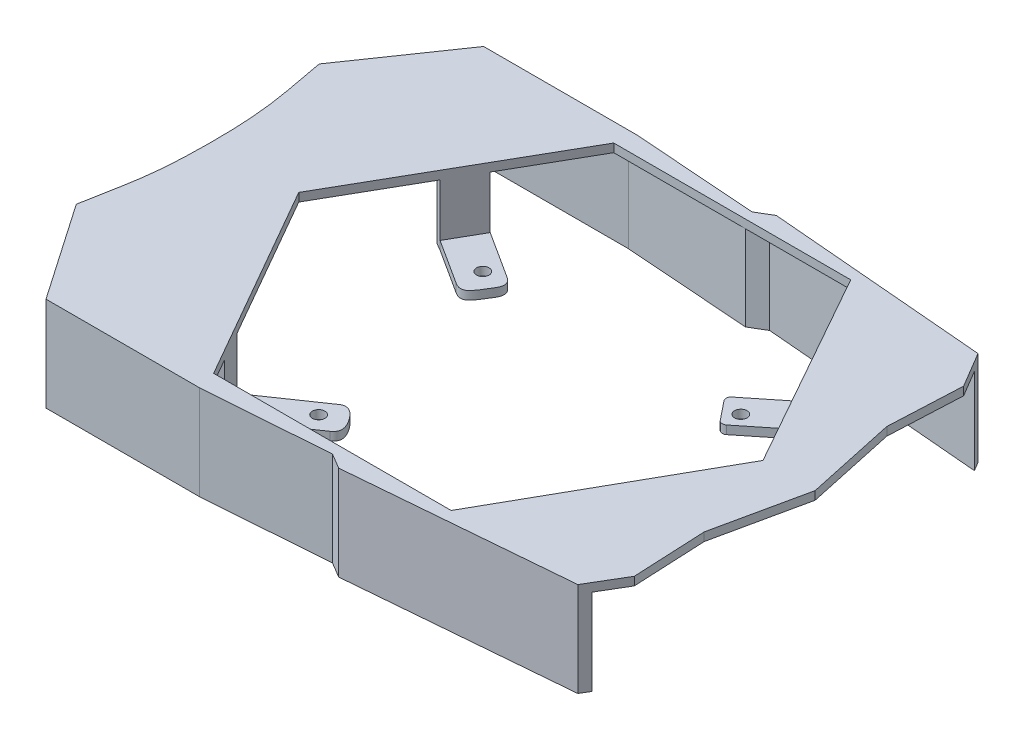
SolidWorks part; units mm, degrees
ref_plane "Front Plane" through (0, 0, 0) normal (0, 0, 1) x (1, 0, 0)
ref_plane "Top Plane" through (0, 0, 0) normal (0, 1, 0) x (1, 0, 0)
ref_plane "Right Plane" through (0, 0, 0) normal (1, 0, 0) x (0, 0, -1)
ref_plane "Plane1" through (0, -1, 0) normal (0, 1, 0) x (1, 0, 0)
sketch "Sketch2" plane through (0, 0, 0) normal (0, 1, 0) x (1, 0, 0)
  line L0 (-43.2305, 45.2477) -> (-32.0512, 38.0628)
  line L1 (-59.8574, 16.2204) -> (-32.6384, -31.2986) construction
  line L2 (-32.6384, -31.2986) -> (24.1663, -31.2986) construction
  line L3 (24.1663, -31.2986) -> (50.8521, 16.2204) construction
  line L4 (50.8521, 16.2204) -> (-59.8574, 16.2204) construction
  line L5 (24.1663, 63.7393) -> (50.8521, 16.2204) construction
  line L6 (-59.8574, 16.2204) -> (-32.6384, 63.7393) construction
  line L7 (-32.6384, 63.7393) -> (24.1663, 63.7393) construction
  line L8 (-47.5869, 37.6421) -> (-36.7839, 30.699)
  line L9 (-43.2305, 45.2477) -> (-47.5869, 37.6421)
  line L10 (-36.7839, 30.699) -> (-32.0512, 38.0628) construction
  line L11 (-34.4176, 34.3809) -> (-25.2787, 28.5074) construction
  line L12 (-32.1914, 32.9502) -> (-30.5732, 35.4679) construction
  line L13 (-36.1854, -25.1061) -> (-21.2791, -14.8713)
  line L14 (-25.7957, -8.2932) -> (-40.1647, -18.159)
  line L15 (-21.2791, -14.8713) -> (-25.7957, -8.2932) construction
  line L16 (-23.5374, -11.5822) -> (-16.1776, -6.5289) construction
  line L17 (29.2117, -22.3145) -> (14.8692, -14.26)
  line L18 (14.6527, -12.323) -> (19.1605, -8.2533)
  line L19 (20.5522, -8.0977) -> (33.2051, -15.2033)
  line L20 (35.9563, 42.7452) -> (24.663, 33.699)
  line L21 (31.8845, 49.9957) -> (19.5337, 40.1025)
  line L22 (22.9762, 33.8854) -> (19.3473, 38.4157)
  line L23 (31.8845, 49.9957) -> (35.9563, 42.7452)
  line L24 (29.2117, -22.3145) -> (33.2051, -15.2033)
  line L25 (-40.1647, -18.159) -> (-36.1854, -25.1061)
  circle A0 centre (-36.0903, 36.3367) radius 1.5
  circle A1 centre (24.1663, 37.603) radius 1.5
  circle A2 centre (19.9954, -13.2346) radius 1.5
  circle A3 centre (-26.0794, -12.8178) radius 1.5
  arc A4 (20.5522, -8.0977) -> (19.1605, -8.2533) centre (19.9646, -9.144) ccw
  arc A5 (14.8692, -14.26) -> (14.6527, -12.323) centre (15.4568, -13.2137) cw
  arc A6 (19.5337, 40.1025) -> (19.3473, 38.4157) centre (20.2839, 39.1659) ccw
  arc A7 (24.663, 33.699) -> (22.9762, 33.8854) centre (23.9128, 34.6356) cw
  spline S0 degree 3 poles (-32.0512, 38.0628) (-29.6539, 36.522) (-32.3592, 33.058) (-34.3933, 29.1626) (-36.7839, 30.699) knots 0 0 0 0 0.5 1 1 1 1
  spline S1 degree 3 poles (-25.7957, -8.2932) (-24.1437, -7.1589) (-21.1111, -9.9163) (-19.5185, -13.6625) (-21.2791, -14.8713) knots 0 0 0 0 0.5 1 1 1 1
  dimension "D1" = 3
  dimension "D2" = 3
  dimension "D3" = 3
  dimension "D4" = 3
  dimension "D19" = 1.2
  dimension "D20" = 1.2
  dimension "D5" = 71.1821
  dimension "D6" = 19.9954
  dimension "D7" = 24.1663
  dimension "D8" = 26.0794
  dimension "D9" = 37.603
  dimension "D10" = 110.7095
  dimension "D11" = 36.3367
  dimension "D12" = 60.196
  dimension "D13" = 74.8527
  dimension "D14" = 31.2986
  dimension "D15" = 36.0903
  dimension "D16" = 32.6384
  dimension "D17" = 24.1663
  dimension "D18" = 50.8521
extrude "Boss-Extrude3" add sketch "Sketch2" along normal blind 2
sketch "Sketch7" plane through (0, 0, 0) normal (0, -1, 0) x (1, 0, 0)
  line L0 (-36.1854, 25.1061) -> (-37.9209, 26.1002)
  line L1 (-37.9209, 26.1002) -> (-41.9002, 19.1531)
  line L2 (-41.9002, 19.1531) -> (-40.1647, 18.159)
  line L3 (-40.1647, 18.159) -> (-36.1854, 25.1061) construction
  line L4 (-40.1647, 18.159) -> (-36.1854, 25.1061) construction
  line L5 (-36.1854, 25.1061) -> (-40.1647, 18.159)
  line L6 (-43.2305, -45.2477) -> (-47.5869, -37.6421)
  line L7 (-43.2305, -45.2477) -> (-44.9659, -46.2417)
  line L8 (-47.5869, -37.6421) -> (-49.3224, -38.6362)
  line L9 (-44.9659, -46.2417) -> (-49.3224, -38.6362)
  line L10 (31.8845, -49.9957) -> (35.9563, -42.7452)
  line L11 (31.8845, -49.9957) -> (33.6283, -50.975)
  line L12 (35.9563, -42.7452) -> (37.7001, -43.7245)
  line L13 (33.6283, -50.975) -> (37.7001, -43.7245)
  line L14 (29.2117, 22.3145) -> (33.2051, 15.2033)
  line L15 (29.2117, 22.3145) -> (30.9555, 23.2938)
  line L16 (33.2051, 15.2033) -> (34.949, 16.1826)
  line L17 (30.9555, 23.2938) -> (34.949, 16.1826)
  line L18 (29.2117, 22.3145) -> (33.2051, 15.2033) construction
  line L19 (33.2051, 15.2033) -> (20.5522, 8.0977) construction
  dimension "D1" = 2
  dimension "D2" = 2
  dimension "D3" = 2
  dimension "D4" = 2
extrude "Boss-Extrude7" add sketch "Sketch7" against normal blind 14.5
sketch "Sketch8" plane through (0, 14.5, 0) normal (0, 1, 0) x (1, 0, 0)
  line L1 (-59.8574, 16.2204) -> (-40.1647, -18.159)
  line L2 (-40.1647, -18.159) -> (-36.1854, -25.1061) construction
  line L3 (-59.8574, 16.2204) -> (50.8334, 16.2204) construction
  line L4 (50.8334, 16.2204) -> (23.9934, -31.2876)
  line L5 (23.9934, -31.2876) -> (-32.6446, -31.2876)
  line L6 (-32.6446, -31.2876) -> (-40.1647, -18.159)
  line L7 (-83.939, -12.7437) -> (-67.9484, -35.9533)
  line L8 (-67.9484, -35.9533) -> (-31.3331, -35.9533)
  line L9 (-31.3331, -35.9533) -> (-1.8009, -33.7876)
  line L10 (-1.8009, -33.7876) -> (1.845, -35.9533)
  line L11 (1.845, -35.9533) -> (54.3929, -31.4855)
  line L12 (54.3929, -31.4855) -> (59.4091, -23.0409)
  line L13 (59.4091, -23.0409) -> (58.5857, -5.538)
  line L14 (58.5857, -5.538) -> (63.2776, 16.2204)
  line L15 (-83.939, -12.7437) -> (-82.229, -3.4871)
  line L16 (-59.8574, 16.2204) -> (-80.6714, 16.2204) construction
  line L17 (-80.6714, 17.2536) -> (-80.6714, 15.1871)
  line L18 (-83.939, 45.1845) -> (-82.229, 35.9279)
  line L19 (58.5857, 37.9787) -> (63.2776, 16.2204)
  line L20 (59.4091, 55.4817) -> (58.5857, 37.9787)
  line L21 (54.3929, 63.9263) -> (59.4091, 55.4817)
  line L22 (1.845, 68.3941) -> (54.3929, 63.9263)
  line L23 (-1.8009, 66.2284) -> (1.845, 68.3941)
  line L24 (-31.3331, 68.3941) -> (-1.8009, 66.2284)
  line L25 (-67.9484, 68.3941) -> (-31.3331, 68.3941)
  line L26 (-83.939, 45.1845) -> (-67.9484, 68.3941)
  line L27 (-32.5028, 63.976) -> (-59.8574, 16.2204)
  line L28 (23.9939, 63.976) -> (-32.5028, 63.976)
  line L29 (50.8334, 16.2204) -> (23.9939, 63.976)
  line L31 (-43.2305, 45.2477) -> (-47.5869, 37.6421) construction
  spline S0 degree 3 poles (-82.229, -3.4871) (-81.0799, 2.7333) (-80.6714, 8.9003) (-80.6714, 15.1871) knots 0 0 0 0 1 1 1 1
  spline S1 degree 3 poles (-82.229, 35.9279) (-81.0799, 29.7075) (-80.6714, 23.5404) (-80.6714, 17.2536) knots 0 0 0 0 1 1 1 1
  dimension "D1" = 2.5
  dimension "D2" = 50.008
  dimension "D3" = 47.7556
  dimension "D4" = 52.1737
  dimension "D5" = 1.0332
extrude "Boss-Extrude8" add sketch "Sketch8" along normal blind 2
sketch "Sketch9" plane through (0, 14.5, 0) normal (0, -1, 0) x (1, 0, 0)
  line L11 (-67.9484, -66.3941) -> (-69.3263, -66.3941)
  line L12 (-67.9484, -68.3941) -> (-83.939, -45.1845) construction
  line L13 (54.2235, -61.9335) -> (55.6486, -61.8123)
  line L14 (59.4091, -55.4817) -> (54.3929, -63.9263) construction
  line L15 (54.2235, -61.9335) -> (2.3148, -66.3469)
  line L16 (2.3148, -66.3469) -> (-1.3201, -64.1877)
  line L17 (-1.3201, -64.1877) -> (-31.4064, -66.3941)
  line L18 (-31.4064, -66.3941) -> (-67.9484, -66.3941)
  line L19 (54.2235, -61.9335) -> (2.3148, -66.3469)
  line L20 (2.3148, -66.3469) -> (-1.3201, -64.1877)
  line L21 (-1.3201, -64.1877) -> (-31.4064, -66.3941)
  line L22 (-31.4064, -66.3941) -> (-67.9484, -66.3941)
  line L33 (-67.9484, 33.9533) -> (-69.3263, 33.9533)
  line L34 (-83.939, 12.7437) -> (-67.9484, 35.9533) construction
  line L35 (54.2235, 29.4927) -> (55.6486, 29.3715)
  line L36 (54.3929, 31.4855) -> (59.4091, 23.0409) construction
  line L37 (2.3148, 33.9062) -> (54.2235, 29.4927)
  line L38 (-1.3201, 31.747) -> (2.3148, 33.9062)
  line L39 (-31.4064, 33.9533) -> (-1.3201, 31.747)
  line L40 (-67.9484, 33.9533) -> (-31.4064, 33.9533)
  line L41 (2.3148, 33.9062) -> (54.2235, 29.4927)
  line L42 (-1.3201, 31.747) -> (2.3148, 33.9062)
  line L43 (-31.4064, 33.9533) -> (-1.3201, 31.747)
  line L44 (-67.9484, 33.9533) -> (-31.4064, 33.9533)
  line L45 (-69.3263, 33.9533) -> (-67.9484, 35.9533)
  line L46 (-67.9484, 35.9533) -> (-31.3331, 35.9533)
  line L47 (-31.3331, 35.9533) -> (-1.8009, 33.7876) construction
  line L48 (-67.9484, 35.9533) -> (-31.3331, 35.9533) construction
  line L49 (-31.3331, 35.9533) -> (-1.8009, 33.7876)
  line L50 (-1.8009, 33.7876) -> (1.845, 35.9533)
  line L51 (1.845, 35.9533) -> (54.3929, 31.4855)
  line L52 (54.3929, 31.4855) -> (55.6486, 29.3715)
  line L53 (55.6486, -61.8123) -> (54.3929, -63.9263)
  line L54 (54.3929, -63.9263) -> (1.845, -68.3941)
  line L55 (1.845, -68.3941) -> (-1.8009, -66.2284)
  line L56 (-1.8009, -66.2284) -> (-31.3331, -68.3941)
  line L57 (-31.3331, -68.3941) -> (-67.9484, -68.3941)
  line L58 (-67.9484, -68.3941) -> (-69.3263, -66.3941)
  dimension "D1" = 2
  dimension "D2" = 2
extrude "Boss-Extrude9" add sketch "Sketch9" along normal blind 20.5
